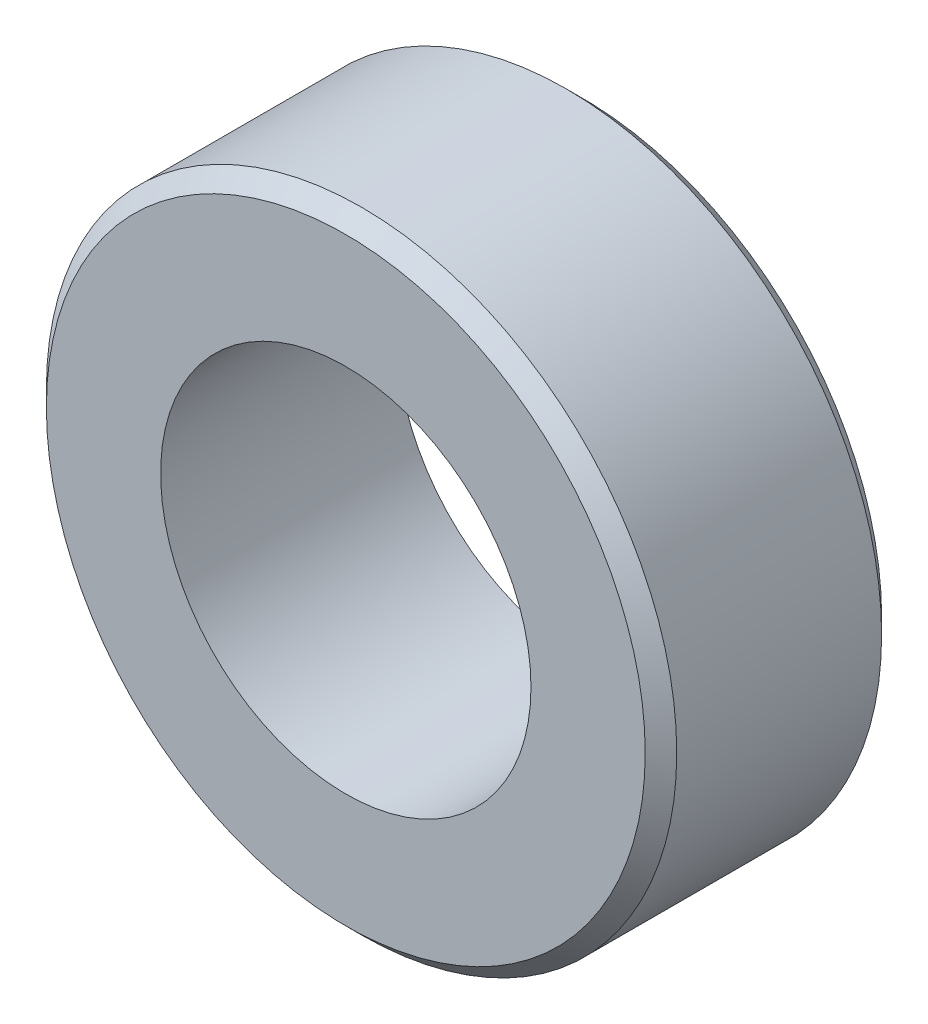
SolidWorks part; units mm, degrees
ref_plane "Front Plane" through (0, 0, 0) normal (0, 0, 1) x (1, 0, 0)
ref_plane "Top Plane" through (0, 0, 0) normal (0, 1, 0) x (1, 0, 0)
ref_plane "Right Plane" through (0, 0, 0) normal (1, 0, 0) x (0, 0, -1)
sketch "Sketch2" plane through (0, 0, 0) normal (0, 0, 1) x (1, 0, 0)
  circle A0 centre (0, 0) radius 23.5
  circle A1 centre (0, 0) radius 40
extrude "Boss-Extrude1" add sketch "Sketch2" along normal blind 30
chamfer "Chamfer1" distance 2 angle 45 2 edges at (40, 0, 30) (40, 0, 0)
